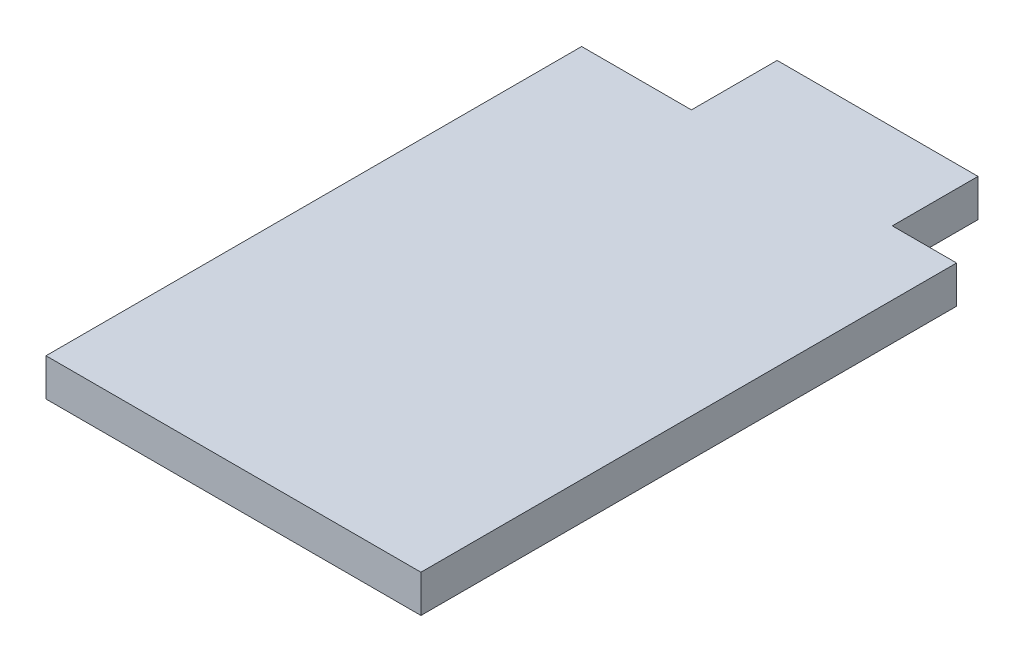
SolidWorks part; units mm, degrees
ref_plane "Front Plane" through (0, 0, 0) normal (0, 0, 1) x (1, 0, 0)
ref_plane "Top Plane" through (0, 0, 0) normal (0, 1, 0) x (1, 0, 0)
ref_plane "Right Plane" through (0, 0, 0) normal (1, 0, 0) x (0, 0, -1)
sketch "Sketch1" plane through (0, 0, 0) normal (0, 1, 0) x (1, 0, 0)
  line L1 (-35, -50) -> (35, -50)
  line L2 (-35, -50) -> (-35, 50)
  line L3 (-35, 50) -> (35, 50)
  line L4 (35, -50) -> (35, 50)
  line L5 (-35, -50) -> (35, 50) construction
  line L6 (-35, 50) -> (35, -50) construction
  point P0 (0, 0)
  dimension "D1" = 70
  dimension "D2" = 100
extrude "Boss-Extrude1" add sketch "Sketch1" along normal blind 7
sketch "Sketch2" plane through (0, 0, 0) normal (0, -1, 0) x (1, 0, 0)
  line L0 (-30.5, 1.5) -> (-35, 1.5) construction
  line L1 (-30.5, -36.5) -> (30.5, -36.5) construction
  line L2 (-30.5, -36.5) -> (-30.5, 39.5) construction
  line L3 (-30.5, 39.5) -> (30.5, 39.5) construction
  line L4 (30.5, -36.5) -> (30.5, 39.5) construction
  line L5 (-35, -50) -> (-35, 50) construction
  line L6 (30.5, 1.5) -> (35, 1.5) construction
  line L7 (35, 50) -> (35, -50) construction
  line L8 (35, -50) -> (-35, -50) construction
  circle A0 centre (-30.5, -36.5) radius 1.5
  circle A1 centre (-30.5, 39.5) radius 1.5
  circle A2 centre (30.5, 39.5) radius 1.5
  circle A3 centre (30.5, -36.5) radius 1.5
  dimension "D1" = 3
  dimension "D2" = 76
  dimension "D3" = 61
  dimension "D4" = 13.5
extrude "Cut-Extrude1" cut sketch "Sketch2" against normal blind 5
sketch "Sketch3" plane through (0, 0, 0) normal (0, -1, 0) x (1, 0, 0)
  line L0 (35, -50) -> (-35, -50) construction
  line L1 (-14.5, -50) -> (23, -50)
  line L2 (-14.5, -50) -> (-14.5, -66)
  line L3 (-14.5, -66) -> (23, -66)
  line L4 (23, -50) -> (23, -66)
  line L5 (-35, -50) -> (-35, 50) construction
  dimension "D1" = 16
  dimension "D2" = 37.5
  dimension "D3" = 20.5
extrude "Boss-Extrude2" add sketch "Sketch3" against normal blind 7
